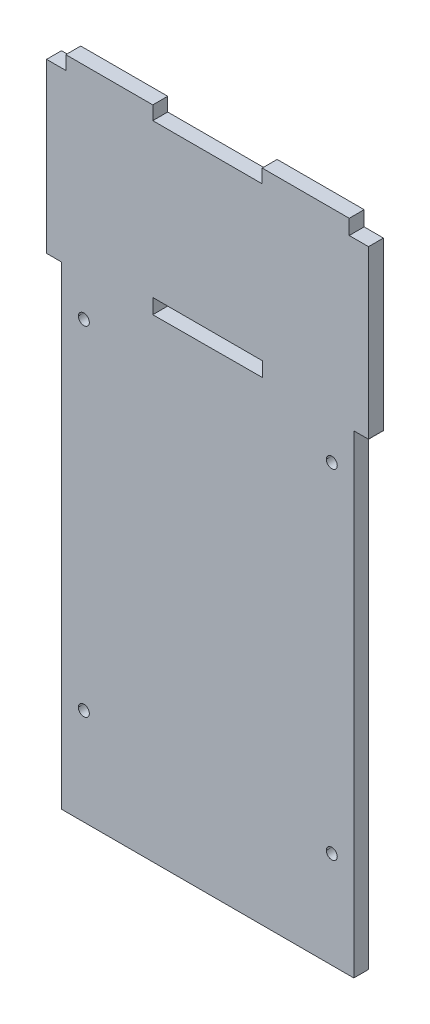
SolidWorks part; units mm, degrees
ref_plane "Front Plane" through (0, 0, 0) normal (0, 0, 1) x (1, 0, 0)
ref_plane "Top Plane" through (0, 0, 0) normal (0, 1, 0) x (1, 0, 0)
ref_plane "Right Plane" through (0, 0, 0) normal (1, 0, 0) x (0, 0, -1)
sketch "Model" plane through (0, 0, 0) normal (0, 0, 1) x (1, 0, 0)
  line L0 (1184.2963, -971.1293) -> (1184.2963, -975.6293)
  line L1 (1244.8584, -975.6293) -> (1244.8584, -1118.4058)
  line L2 (1244.8584, -1118.4058) -> (1156.7232, -1118.4058)
  line L3 (1156.7232, -1118.4058) -> (1156.7232, -975.6293)
  line L4 (1244.8584, -975.6293) -> (1249.2909, -975.6293)
  line L5 (1249.2909, -975.6293) -> (1249.2901, -975.557)
  line L6 (1249.2901, -975.557) -> (1249.2901, -952.0821)
  line L7 (1249.2901, -952.0821) -> (1249.2901, -925.3764)
  line L8 (1249.2901, -925.3764) -> (1243.4769, -925.3764)
  line L9 (1184.2963, -975.6293) -> (1217.2852, -975.5026)
  line L11 (1184.2963, -971.1293) -> (1217.2852, -971.1293)
  line L12 (1217.2852, -971.1293) -> (1217.2852, -975.5026)
  line L13 (1243.4769, -925.3764) -> (1243.4769, -920.8792)
  line L14 (1243.4769, -920.8792) -> (1217.2649, -920.8792)
  line L15 (1217.2649, -920.8792) -> (1217.2649, -924.9988)
  line L16 (1217.2649, -924.9988) -> (1184.2957, -924.9988)
  line L17 (1184.2957, -924.9988) -> (1184.2957, -920.8792)
  line L18 (1184.2957, -920.8792) -> (1158.0836, -920.8792)
  line L19 (1158.0836, -920.8792) -> (1158.0836, -924.9988)
  line L20 (1158.0836, -924.9988) -> (1152.2907, -924.9988)
  line L21 (1152.2907, -924.9988) -> (1152.2907, -925.7292)
  line L22 (1152.2907, -925.7292) -> (1152.2907, -950.671)
  line L23 (1152.2907, -950.671) -> (1152.2907, -975.557)
  line L24 (1152.2907, -975.557) -> (1152.2907, -975.6293)
  line L25 (1152.2907, -975.6293) -> (1156.7232, -975.6293)
  spline S0 degree 3 poles (1239.8733, -1089.2558) (1239.8733, -1090.167) (1239.1347, -1090.9057) (1238.2231, -1090.9057) (1237.3122, -1090.9057) (1236.5729, -1090.167) (1236.5729, -1089.2558) knots 2 2 2 2 3 3 3 4 4 4 4
  spline S1 degree 3 poles (1236.5729, -1089.2558) (1236.5729, -1088.3446) (1237.3122, -1087.6056) (1238.2231, -1087.6056) (1239.1347, -1087.6056) (1239.8733, -1088.3446) (1239.8733, -1089.2558) knots 0 0 0 0 1 1 1 2 2 2 2
  spline S2 degree 3 poles (1165.1733, -1089.2558) (1165.1733, -1090.167) (1164.4347, -1090.9057) (1163.5231, -1090.9057) (1162.6123, -1090.9057) (1161.8729, -1090.167) (1161.8729, -1089.2558) knots 2 2 2 2 3 3 3 4 4 4 4
  spline S3 degree 3 poles (1161.8729, -1089.2558) (1161.8729, -1088.3446) (1162.6123, -1087.6056) (1163.5231, -1087.6056) (1164.4347, -1087.6056) (1165.1733, -1088.3446) (1165.1733, -1089.2558) knots 0 0 0 0 1 1 1 2 2 2 2
  spline S4 degree 3 poles (1239.8733, -987.2076) (1239.8733, -988.1192) (1239.1347, -988.8578) (1238.2231, -988.8578) (1237.3122, -988.8578) (1236.5729, -988.1192) (1236.5729, -987.2076) knots 2 2 2 2 3 3 3 4 4 4 4
  spline S5 degree 3 poles (1236.5729, -987.2076) (1236.5729, -986.2967) (1237.3122, -985.5577) (1238.2231, -985.5577) (1239.1347, -985.5577) (1239.8733, -986.2967) (1239.8733, -987.2076) knots 0 0 0 0 1 1 1 2 2 2 2
  spline S6 degree 3 poles (1165.173, -987.2076) (1165.173, -988.1192) (1164.4344, -988.8578) (1163.5228, -988.8578) (1162.6119, -988.8578) (1161.8726, -988.1192) (1161.8726, -987.2076) knots 2 2 2 2 3 3 3 4 4 4 4
  spline S7 degree 3 poles (1161.8726, -987.2076) (1161.8726, -986.2967) (1162.6119, -985.5577) (1163.5228, -985.5577) (1164.4344, -985.5577) (1165.173, -986.2967) (1165.173, -987.2076) knots 0 0 0 0 1 1 1 2 2 2 2
extrude "Boss-Extrude1" add sketch "Model" along normal blind 4.5
